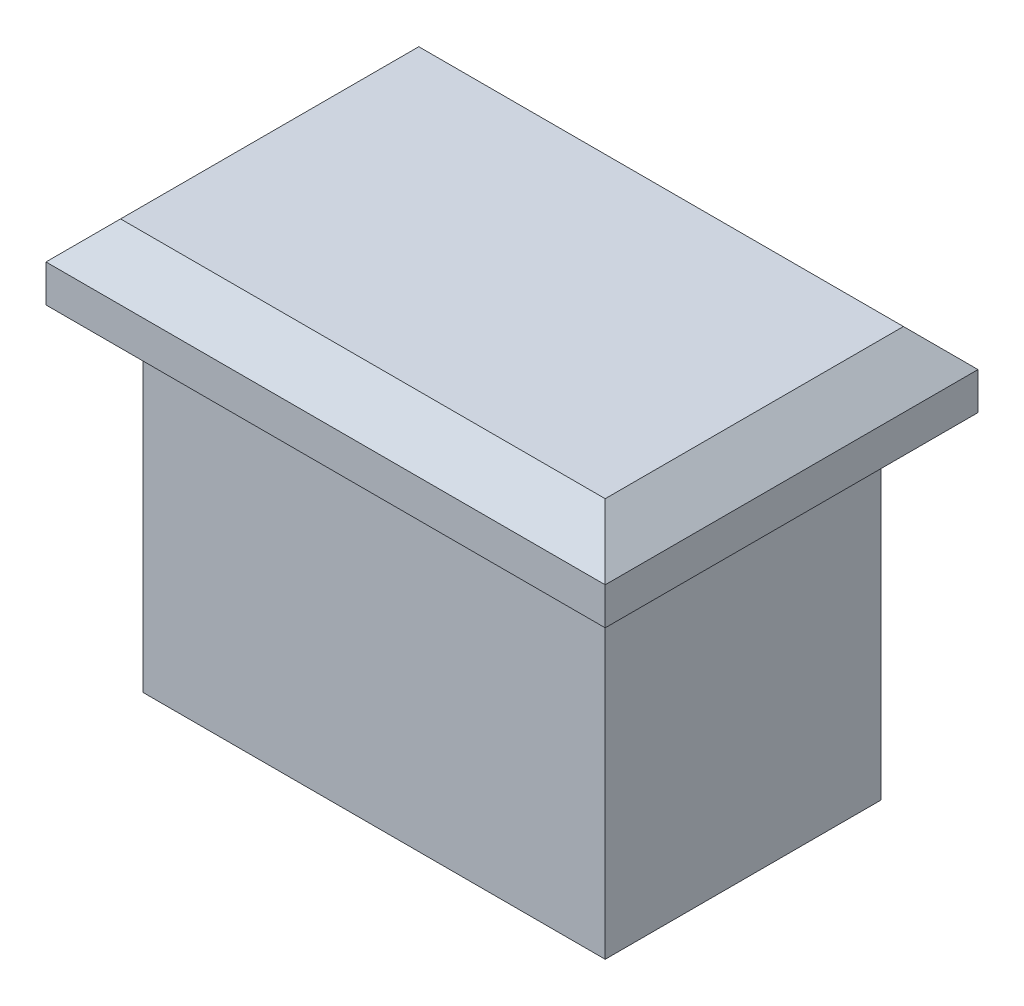
SolidWorks part; units mm, degrees
ref_plane "正面" through (0, 0, 0) normal (0, 0, 1) x (1, 0, 0)
ref_plane "平面" through (0, 0, 0) normal (0, 1, 0) x (1, 0, 0)
ref_plane "右側面" through (0, 0, 0) normal (1, 0, 0) x (0, 0, -1)
sketch "ｽｹｯﾁ1" plane through (0, 0, 0) normal (0, 1, 0) x (1, 0, 0)
  line L0 (-6.2, 3.7) -> (6.2, 3.7)
  line L5 (-7.5, 5) -> (7.5, 5)
  line L6 (-7.5, 5) -> (-7.5, -5)
  line L7 (-7.5, -5) -> (7.5, -5)
  line L8 (7.5, 5) -> (7.5, -5)
  line L9 (-7.5, 5) -> (7.5, -5) construction
  line L10 (-7.5, -5) -> (7.5, 5) construction
  line L11 (6.2, 3.7) -> (6.2, -3.7)
  line L12 (-6.2, -3.7) -> (6.2, -3.7)
  line L13 (-6.2, 3.7) -> (-6.2, -3.7)
  point P0 (0, 0)
  dimension "D1" = 10
  dimension "D2" = 15
  dimension "D3" = 1.3
extrude "ﾎﾞｽ - 押し出し1" add sketch "ｽｹｯﾁ1" along normal blind 2 contours L0 L13 L12 L11 | L8 L5 L6 L7 L13 L0 L11 L12
sketch "ｽｹｯﾁ2" plane through (0, 0, 0) normal (0, -1, 0) x (1, 0, 0)
  line L4 (-7.5, -5) -> (7.5, -5)
  line L5 (7.5, -5) -> (7.5, 5)
  line L6 (7.5, 5) -> (-7.5, 5)
  line L7 (-7.5, 5) -> (-7.5, -5)
  line L8 (-7.5, -5) -> (7.5, -5)
  line L9 (7.5, -5) -> (7.5, 5)
  line L10 (7.5, 5) -> (-7.5, 5)
  line L11 (-7.5, 5) -> (-7.5, -5)
  line L12 (-6.2, -3.7) -> (6.2, -3.7)
  line L13 (6.2, -3.7) -> (6.2, 3.7)
  line L14 (6.2, 3.7) -> (-6.2, 3.7)
  line L15 (-6.2, 3.7) -> (-6.2, -3.7)
  line L16 (-6.2, -3.7) -> (6.2, -3.7)
  line L17 (6.2, -3.7) -> (6.2, 3.7)
  line L18 (6.2, 3.7) -> (-6.2, 3.7)
  line L19 (-6.2, 3.7) -> (-6.2, -3.7)
  dimension "D1" = 0
  dimension "D2" = 0
extrude "ﾎﾞｽ - 押し出し2" add sketch "ｽｹｯﾁ2" along normal blind 10 contours L18 L19 L16 L17
chamfer "面取り1" distance 1 angle 45 4 edges at (6.2, -10, 0) (0, -10, -3.7) (-6.2, -10, 0) (0, -10, 3.7)
chamfer "面取り2" distance 1 angle 45 4 edges at (0, 2, 5) (-7.5, 2, 0) (0, 2, -5) (7.5, 2, 0)
